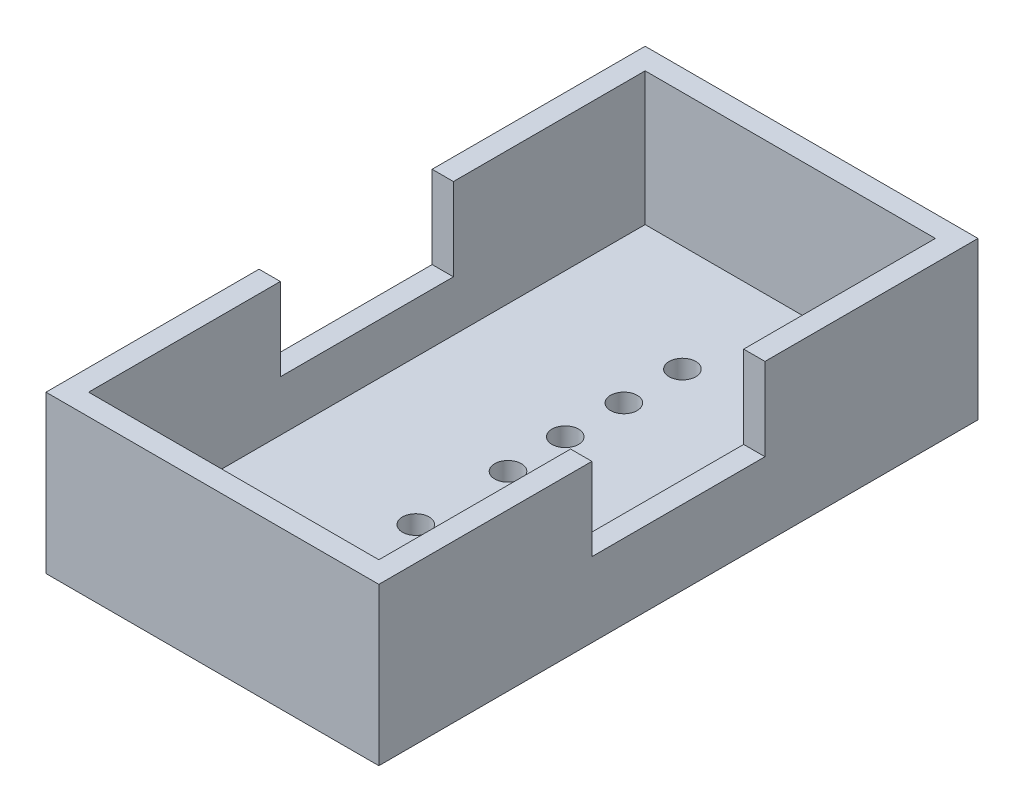
SolidWorks part; units mm, degrees
material "ABS"
ref_plane "Front Plane" through (0, 0, 0) normal (0, 0, 1) x (1, 0, 0)
ref_plane "Top Plane" through (0, 0, 0) normal (0, 1, 0) x (1, 0, 0)
ref_plane "Right Plane" through (0, 0, 0) normal (1, 0, 0) x (0, 0, -1)
sketch "Sketch1" plane through (0, 0, 0) normal (0, 1, 0) x (1, 0, 0)
  line L1 (-15.875, 28.575) -> (15.875, 28.575)
  line L2 (-15.875, 28.575) -> (-15.875, -28.575)
  line L3 (-15.875, -28.575) -> (15.875, -28.575)
  line L4 (15.875, 28.575) -> (15.875, -28.575)
  line L5 (-15.875, 28.575) -> (15.875, -28.575) construction
  line L6 (-15.875, -28.575) -> (15.875, 28.575) construction
  point P0 (0, 0)
  dimension "D1" = 31.75
  dimension "D2" = 57.15
extrude "Boss-Extrude1" add sketch "Sketch1" along normal blind 2.286
sketch "Sketch2" plane through (0, 2.286, 0) normal (0, 1, 0) x (1, 0, 0)
  line L0 (-15.875, 28.575) -> (15.875, 28.575)
  line L1 (15.875, 28.575) -> (15.875, -28.575)
  line L2 (15.875, -28.575) -> (-15.875, -28.575)
  line L3 (-15.875, -28.575) -> (-15.875, 28.575)
  line L14 (-13.843, 26.543) -> (-13.843, -26.543)
  line L15 (-13.843, -26.543) -> (13.843, -26.543)
  line L16 (13.843, -26.543) -> (13.843, 26.543)
  line L17 (13.843, 26.543) -> (-13.843, 26.543)
  line L18 (-13.843, 26.543) -> (-13.843, -26.543)
  line L19 (-13.843, -26.543) -> (13.843, -26.543)
  line L20 (13.843, -26.543) -> (13.843, 26.543)
  line L21 (13.843, 26.543) -> (-13.843, 26.543)
  dimension "D1" = 2.032
extrude "Boss-Extrude2" add sketch "Sketch2" along normal blind 12.7
sketch "Sketch3" plane through (0, 2.286, 0) normal (0, 1, 0) x (1, 0, 0)
  line L0 (13.843, 26.543) -> (-13.843, 26.543) construction
  line L1 (-13.843, 26.543) -> (-13.843, -26.543) construction
  circle A0 centre (-0.127, 16.383) radius 1.27
  circle A1 centre (-0.127, 10.795) radius 1.27
  circle A2 centre (-0.127, 5.207) radius 1.27
  circle A3 centre (0, -0.381) radius 1.27
  circle A4 centre (0, -9.177) radius 1.27
  dimension "D1" = 2.54
  dimension "D2" = 10.16
  dimension "D3" = 13.716
  dimension "D4" = 5.588
  dimension "D5" = 5.588
  dimension "D6" = 5.588
extrude "Cut-Extrude1" cut sketch "Sketch3" against normal through all
sketch "Sketch4" plane through (-15.875, 0, 0) normal (-1, 0, 0) x (0, 0, 1)
  line L0 (28.575, 14.986) -> (28.575, 0) construction
  line L1 (-8.255, 14.986) -> (8.255, 14.986)
  line L2 (-8.255, 14.986) -> (-8.255, 7.112)
  line L3 (-8.255, 7.112) -> (8.255, 7.112)
  line L4 (8.255, 14.986) -> (8.255, 7.112)
  line L5 (-8.255, 14.986) -> (8.255, 7.112) construction
  line L6 (-8.255, 7.112) -> (8.255, 14.986) construction
  line L8 (-28.575, 14.986) -> (28.575, 14.986) construction
  point P0 (0, 11.049)
  dimension "D1" = 16.51
  dimension "D2" = 7.874
  dimension "D3" = 20.32
extrude "Cut-Extrude2" cut sketch "Sketch4" against normal through all
